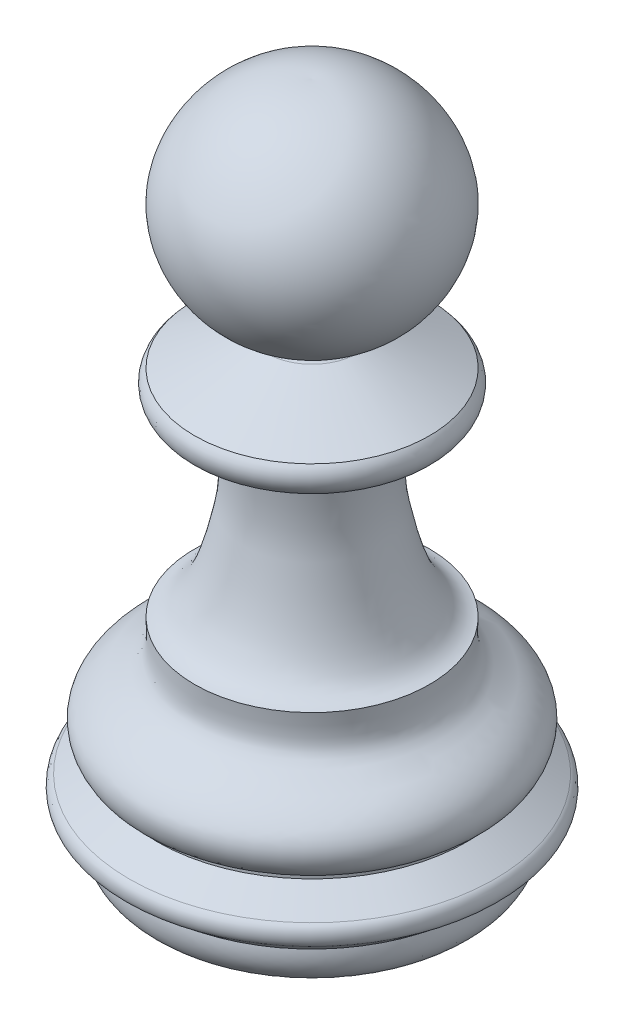
SolidWorks part; units mm, degrees
ref_plane "Plan de face" through (0, 0, 0) normal (0, 0, 1) x (1, 0, 0)
ref_plane "Plan de dessus" through (0, 0, 0) normal (0, 1, 0) x (1, 0, 0)
ref_plane "Plan de droite" through (0, 0, 0) normal (1, 0, 0) x (0, 0, -1)
sketch "Esquisse1" plane through (0, 0, 0) normal (0, 0, 1) x (1, 0, 0)
  line L0 (0, 0) -> (117.15, 0) construction
  line L1 (117.15, 0) -> (117.15, 28.1066) construction
  line L2 (117.15, 0) -> (122.6891, 0)
  line L3 (123.5075, 1.4989) -> (124.42, 2.2306)
  line L4 (124.3455, 2.99) -> (123.2402, 3.7018)
  line L5 (123.2402, 3.7018) -> (123.2402, 3.9163)
  line L6 (119.9195, 15.6769) -> (121.5093, 15.6769)
  line L7 (121.774, 16.8138) -> (118.8345, 18.2518)
  line L8 (118.8345, 18.2518) -> (118.8345, 18.5348)
  line L9 (117.15, 26.6704) -> (117.15, 0)
  spline S0 degree 2 poles (122.6891, 0) (123.7202, 0.4133) (123.5075, 1.4989) knots 0 0 0 1 1 1
  spline S1 degree 3 poles (124.42, 2.2306) (124.425, 2.2346) (124.525, 2.3148) (124.5993, 2.6378) (124.467, 2.9118) (124.3513, 2.9863) (124.3455, 2.99) knots 0 0 0 0 0.024883 0.497653 0.974883 1 1 1 1
  spline S2 degree 3 poles (123.2402, 3.9163) (123.7231, 3.9913) (124.3067, 5.1017) (123.0817, 6.266) (121.685, 6.8378) (121.752, 7.8301) (121.774, 8.3349) knots 0 0 0 0 0.244963 0.538873 0.805632 1 1 1 1
  spline S3 degree 3 poles (121.774, 8.3349) (121.3252, 8.4239) (120.5544, 9.1647) (120.0966, 10.9818) (119.8319, 12.2576) (119.6139, 13.3662) (119.9195, 15.6769) knots 0 0 0 0 0.213513 0.653955 0.738109 1 1 1 1
  spline S4 degree 3 poles (121.5093, 15.6769) (121.5162, 15.6769) (121.6541, 15.6769) (122.0621, 16.0602) (122.0185, 16.5527) (121.774, 16.8138) knots 0 0 0 0 0.015326 0.306515 1 1 1 1
  spline S5 degree 3 poles (118.8345, 18.5348) (120.5249, 18.9707) (122.7737, 22.0643) (120.4038, 26.0127) (118.1295, 26.7339) (117.15, 26.6704) knots 0 0 0 0 0.437276 0.75681 1 1 1 1
  dimension "D1" = 117.15
revolve "Révolution1" add sketch "Esquisse1" angle 360 about L9
fillet "Congé1" radius 0.2 1 edges at (117.15, 18.5348, 1.6845)
fillet "Congé2" radius 0.5 1 edges at (117.15, 15.6769, 2.7695)
fillet "Congé3" radius 0.18 1 edges at (117.15, 18.2518, 1.6845)
